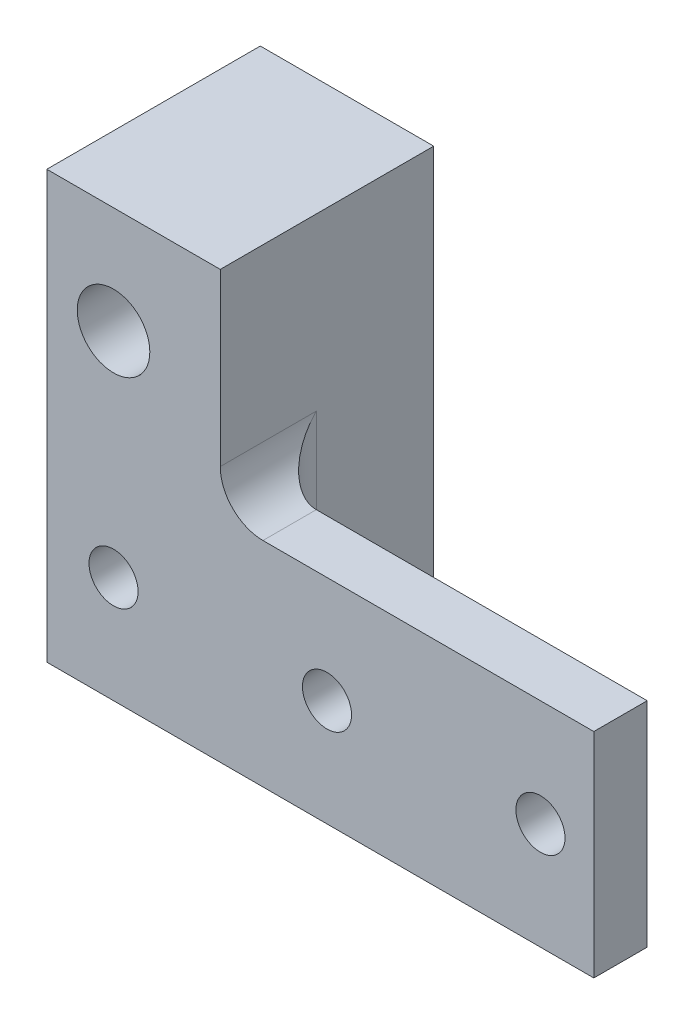
SolidWorks part; units mm, degrees
ref_plane "Front Plane" through (0, 0, 0) normal (0, 0, 1) x (1, 0, 0)
ref_plane "Top Plane" through (0, 0, 0) normal (0, 1, 0) x (1, 0, 0)
ref_plane "Right Plane" through (0, 0, 0) normal (1, 0, 0) x (0, 0, -1)
sketch "Sketch1" plane through (0, 0, 0) normal (0, 0, 1) x (1, 0, 0)
  line L0 (0, 0) -> (0, 50.8)
  line L1 (0, 50.8) -> (25.4, 50.8)
  line L2 (25.4, 50.8) -> (25.4, 25.4)
  line L3 (25.4, 25.4) -> (69.85, 25.4)
  line L4 (69.85, 25.4) -> (69.85, 0)
  line L5 (69.85, 0) -> (0, 0)
  dimension "D1" = 50.8
  dimension "D2" = 25.4
  dimension "2.75" = 69.85
extrude "Boss-Extrude1" add sketch "Sketch1" along normal blind 25.4
sketch "Sketch2" plane through (0, 0, 25.4) normal (0, 0, 1) x (1, 0, 0)
  line L0 (25.4, 50.8) -> (0, 50.8) construction
  line L1 (25.4, 25.4) -> (25.4, 50.8) construction
  line L2 (0, 0) -> (69.85, 0) construction
  circle A0 centre (12.7, 38.1) radius 2.921
  circle A1 centre (12.7, 12.7) radius 2.921
  circle A2 centre (38.1, 12.7) radius 2.921
  circle A3 centre (63.5, 12.7) radius 2.921
  dimension "D1" = 5.842
  dimension "D2" = 12.7
  dimension "D3" = 12.7
  dimension "D4" = 12.7
  dimension "D5" = 3
extrude "Cut-Extrude1" cut sketch "Sketch2" against normal through all
sketch "Sketch3" plane through (0, 0, 25.4) normal (0, 0, 1) x (1, 0, 0)
  line L0 (25.4, 50.8) -> (0, 50.8) construction
  line L1 (0, 0) -> (4.7625, 0)
  line L2 (0, 0) -> (0, 50.8)
  line L3 (0, 50.8) -> (4.7625, 50.8)
  line L4 (4.7625, 0) -> (4.7625, 50.8)
  dimension "D1" = 4.7625
extrude "Cut-Extrude2" cut sketch "Sketch3" against normal through all
sketch "Sketch4" plane through (0, 0, 0) normal (0, -1, 0) x (1, 0, 0)
  line L1 (69.85, 0) -> (25.4, 0)
  line L2 (69.85, 0) -> (69.85, 19.05)
  line L3 (69.85, 19.05) -> (25.4, 19.05)
  line L4 (25.4, 0) -> (25.4, 19.05)
  dimension "D1" = 19.05
  dimension "D2" = 44.45
extrude "Cut-Extrude3" cut sketch "Sketch4" against normal through all
fillet "Fillet1" radius 5.08 2 edges at (25.4, 12.7, 19.05) (25.4, 25.4, 22.225)
sketch "Sketch6" plane through (0, 0, 25.4) normal (0, 0, 1) x (1, 0, 0)
  circle A0 centre (12.7, 38.1) radius 4.318
  dimension "D1" = 8.636
extrude "Cut-Extrude5" cut sketch "Sketch6" against normal blind 12.7
